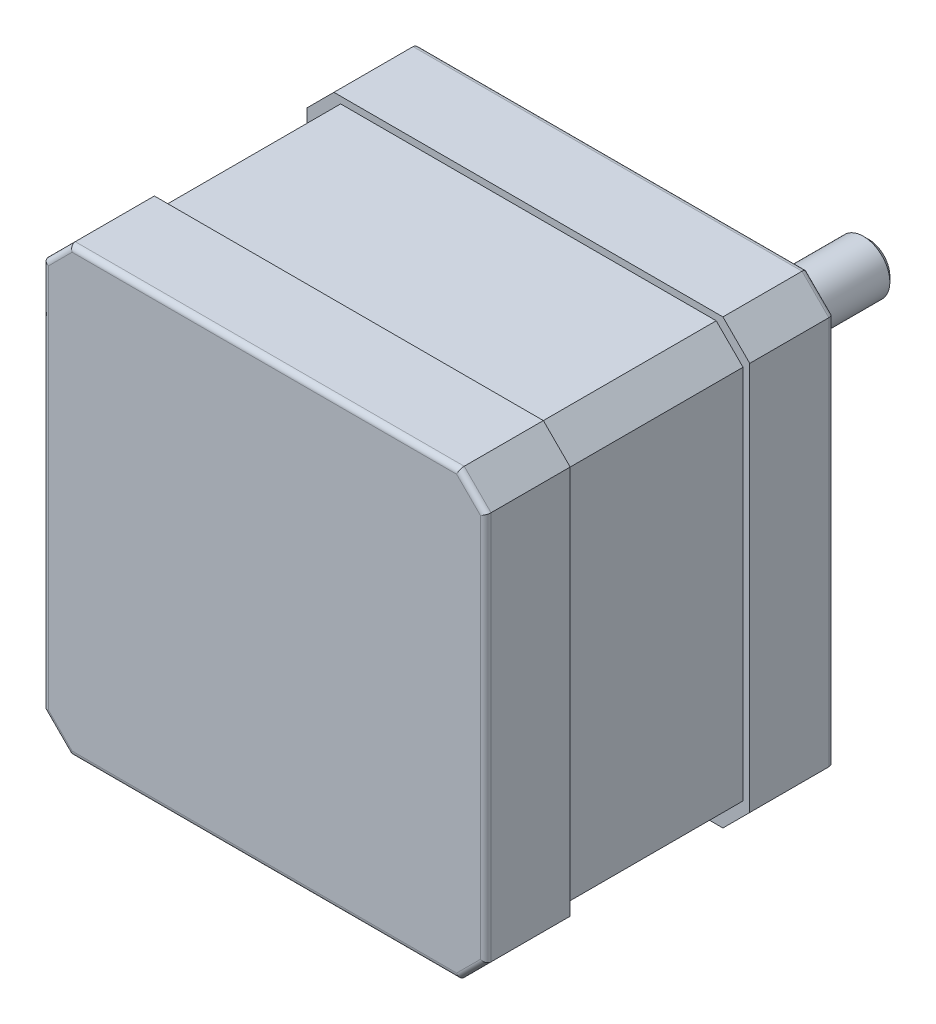
SolidWorks part; units mm, degrees
ref_plane "Front Plane" through (0, 0, 0) normal (0, 0, 1) x (1, 0, 0)
ref_plane "Top Plane" through (0, 0, 0) normal (0, 1, 0) x (1, 0, 0)
ref_plane "Right Plane" through (0, 0, 0) normal (1, 0, 0) x (0, 0, -1)
sketch "Sketch1" plane through (0, 0, 0) normal (0, 0, 1) x (1, 0, 0)
  line L1 (-20.955, -20.955) -> (20.955, -20.955)
  line L2 (-20.955, -20.955) -> (-20.955, 20.955)
  line L3 (-20.955, 20.955) -> (20.955, 20.955)
  line L4 (20.955, -20.955) -> (20.955, 20.955)
  line L5 (-20.955, -20.955) -> (20.955, 20.955) construction
  line L6 (-20.955, 20.955) -> (20.955, -20.955) construction
  point P0 (0, 0)
  dimension "D1" = 41.91
extrude "Boss-Extrude1" add sketch "Sketch1" along normal blind 8
sketch "Sketch2" plane through (0, 0, 8) normal (0, 0, 1) x (1, 0, 0)
  line L1 (-20.32, -20.32) -> (20.32, -20.32)
  line L2 (-20.32, -20.32) -> (-20.32, 20.32)
  line L3 (-20.32, 20.32) -> (20.32, 20.32)
  line L4 (20.32, -20.32) -> (20.32, 20.32)
  line L5 (-20.32, -20.32) -> (20.32, 20.32) construction
  line L6 (-20.32, 20.32) -> (20.32, -20.32) construction
  point P0 (0, 0)
  dimension "D1" = 40.64
extrude "Boss-Extrude2" add sketch "Sketch2" along normal blind 17
sketch "Sketch3" plane through (0, 0, 25) normal (0, 0, 1) x (1, 0, 0)
  line L1 (-20.955, -20.955) -> (20.955, -20.955)
  line L2 (-20.955, -20.955) -> (-20.955, 20.955)
  line L3 (-20.955, 20.955) -> (20.955, 20.955)
  line L4 (20.955, -20.955) -> (20.955, 20.955)
  line L5 (-20.955, -20.955) -> (20.955, 20.955) construction
  line L6 (-20.955, 20.955) -> (20.955, -20.955) construction
  point P0 (0, 0)
extrude "Boss-Extrude3" add sketch "Sketch3" along normal blind 8
chamfer "Chamfer1" distance 2.54 angle 45 4 edges at (20.32, -20.32, 16.5) (-20.32, -20.32, 16.5) (-20.32, 20.32, 16.5) (20.32, 20.32, 16.5)
chamfer "Chamfer2" distance 2.54 angle 45 8 edges at (20.955, 20.955, 29) (20.955, 20.955, 4) (-20.955, 20.955, 4) (-20.955, 20.955, 29) (-20.955, -20.955, 29) (-20.955, -20.955, 4) (20.955, -20.955, 4) (20.955, -20.955, 29)
sketch "Sketch4" plane through (0, 0, 0) normal (0, 0, -1) x (-1, 0, 0)
  circle A0 centre (0, 0) radius 10.9982
  dimension "D1" = 21.9964
extrude "Boss-Extrude4" add sketch "Sketch4" along normal blind 2
sketch "Sketch5" plane through (0, 0, -2) normal (0, 0, -1) x (-1, 0, 0)
  circle A0 centre (0, 0) radius 2.5
  dimension "D1" = 5
extrude "Boss-Extrude5" add sketch "Sketch5" along normal blind 22.225
chamfer "Chamfer3" distance 0.508 angle 45 1 edges at (-2.5, 0, -24.225)
fillet "Fillet2" radius 0.508 17 edges at (19.685, -19.685, 33) (0, -20.955, 33) (-19.685, -19.685, 33) (-20.955, 0, 33) (-19.685, 19.685, 33) (0, 20.955, 33) (19.685, 19.685, 33) (20.955, 0, 33) (-10.9982, 0, 0) (-19.685, 19.685, 0) (-20.955, 0, 0) (-19.685, -19.685, 0) (0, -20.955, 0) (19.685, -19.685, 0) (20.955, 0, 0) (19.685, 19.685, 0) (0, 20.955, 0)
sketch "Sketch6" plane through (0, 0, 0) normal (0, 0, -1) x (-1, 0, 0)
  line L0 (0, 0) -> (19.3258, 19.3258) construction
  line L1 (20.447, 18.2046) -> (18.2046, 20.447) construction
  line L2 (0, 0) -> (-19.3258, -19.3258) construction
  line L3 (-20.447, -18.2046) -> (-18.2046, -20.447) construction
  line L4 (-15.5, -15.5) -> (0, 0) construction
  line L5 (15.5, 15.5) -> (0, 0) construction
  circle A0 centre (15.5, 15.5) radius 1.397
  circle A1 centre (-15.5, -15.5) radius 1.397
  dimension "D1" = 2.794
  dimension "D2" = 31
extrude "Cut-Extrude1" cut sketch "Sketch6" against normal blind 5.08
